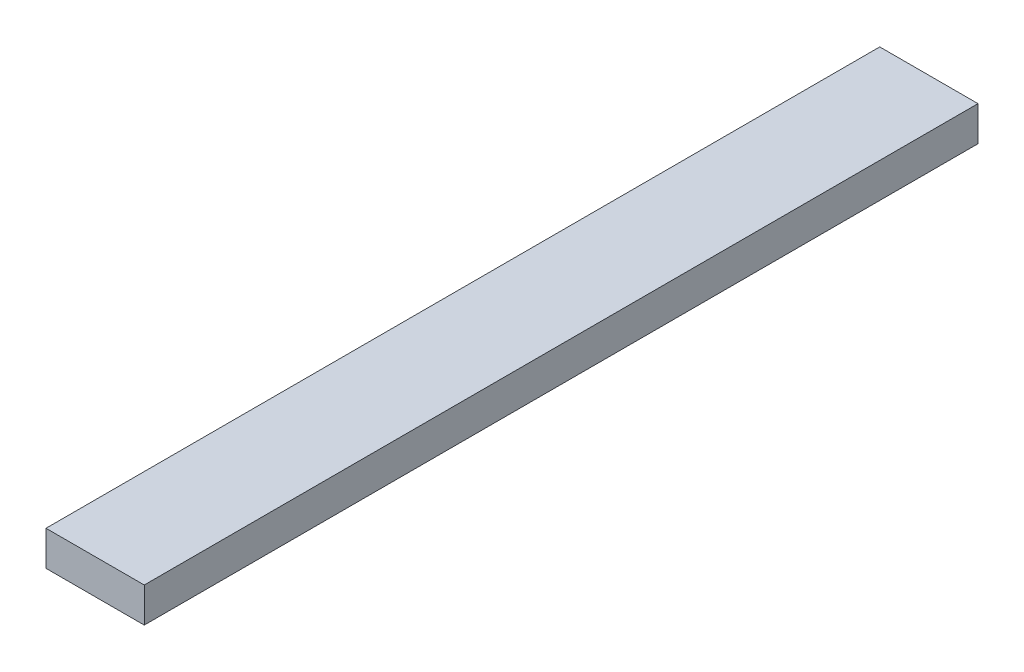
SolidWorks part; units mm, degrees
ref_plane "Front Plane" through (0, 0, 0) normal (0, 0, 1) x (1, 0, 0)
ref_plane "Top Plane" through (0, 0, 0) normal (0, 1, 0) x (1, 0, 0)
ref_plane "Right Plane" through (0, 0, 0) normal (1, 0, 0) x (0, 0, -1)
sketch "Sketch1" plane through (0, 0, 0) normal (0, 0, 1) x (1, 0, 0)
  line L1 (0, 0) -> (17.9605, 0)
  line L2 (0, 0) -> (0, 6.35)
  line L3 (0, 6.35) -> (17.9605, 6.35)
  line L4 (17.9605, 0) -> (17.9605, 6.35)
  dimension "D1" = 6.35
  dimension "D2" = 17.9605
extrude "Boss-Extrude1" add sketch "Sketch1" along normal blind 152.4
